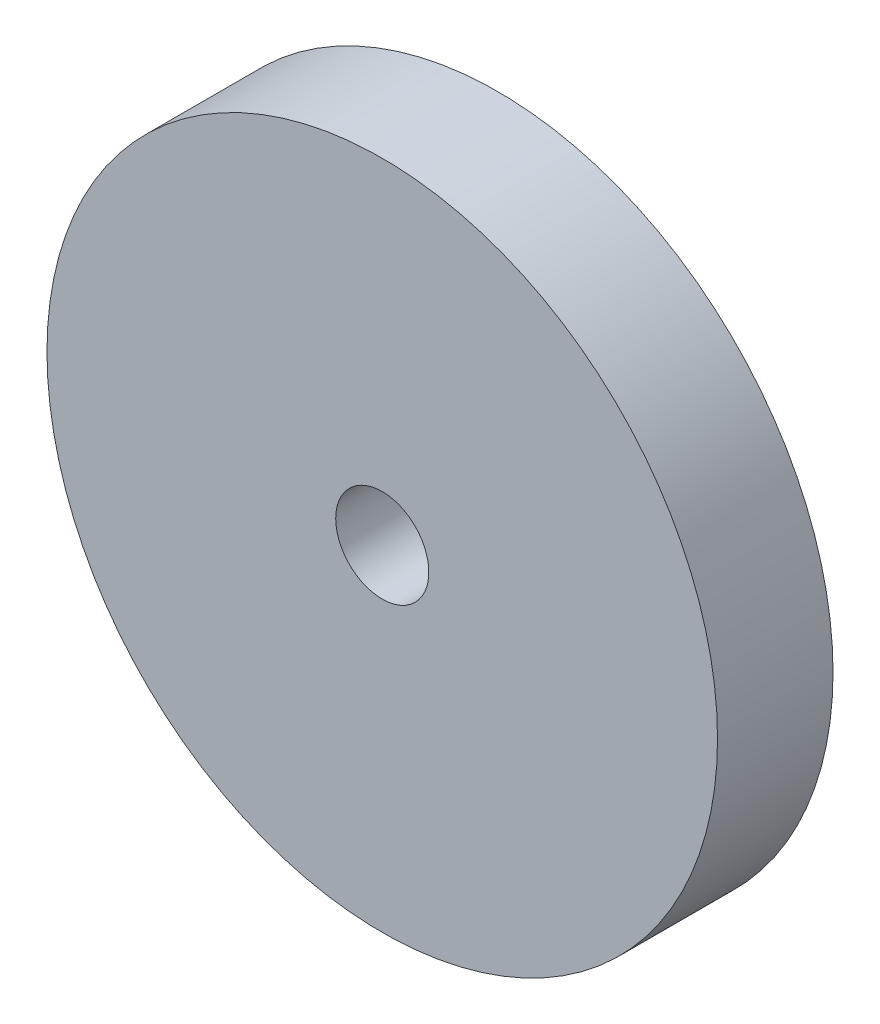
SolidWorks part; units mm, degrees
ref_plane "Front Plane" through (0, 0, 0) normal (0, 0, 1) x (1, 0, 0)
ref_plane "Top Plane" through (0, 0, 0) normal (0, 1, 0) x (1, 0, 0)
ref_plane "Right Plane" through (0, 0, 0) normal (1, 0, 0) x (0, 0, -1)
sketch "Sketch1" plane through (0, 0, 0) normal (0, 0, 1) x (1, 0, 0)
  circle A0 centre (0, 0) radius 18
  circle A1 centre (0, 0) radius 2.5
  dimension "D1" = 5
  dimension "D2" = 36
extrude "Boss-Extrude1" add sketch "Sketch1" along normal blind 6.2
